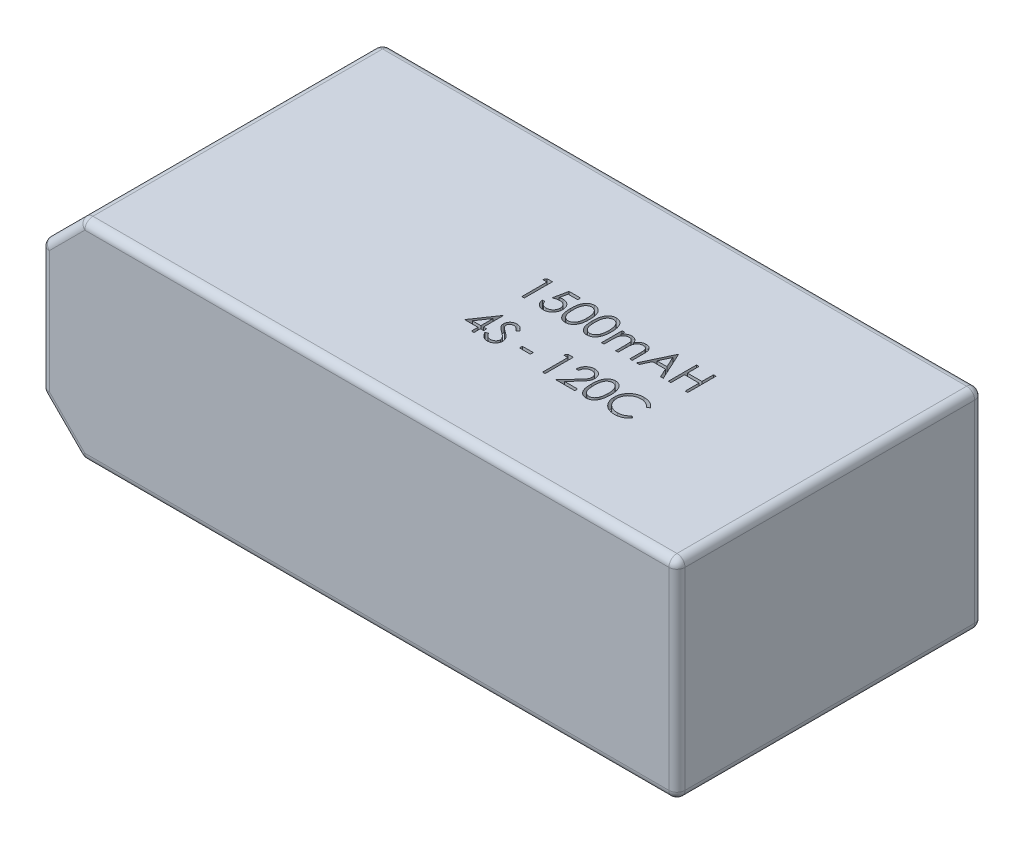
SolidWorks part; units mm, degrees
ref_plane "Front Plane" through (0, 0, 0) normal (0, 0, 1) x (1, 0, 0)
ref_plane "Top Plane" through (0, 0, 0) normal (0, 1, 0) x (1, 0, 0)
ref_plane "Right Plane" through (0, 0, 0) normal (1, 0, 0) x (0, 0, -1)
sketch "Sketch1" plane through (0, 0, 0) normal (0, 1, 0) x (1, 0, 0)
  line L1 (-39.5, -19) -> (39.5, -19)
  line L2 (-39.5, -19) -> (-39.5, 19)
  line L3 (-39.5, 19) -> (39.5, 19)
  line L4 (39.5, -19) -> (39.5, 19)
  line L5 (-39.5, -19) -> (39.5, 19) construction
  line L6 (-39.5, 19) -> (39.5, -19) construction
  point P0 (0, 0)
  dimension "D1" = 79
  dimension "D2" = 38
extrude "Boss-Extrude1" add sketch "Sketch1" along normal mid plane 26
chamfer "Chamfer1" distance 5 angle 45 2 edges at (-39.5, 13, 0) (-39.5, -13, 0)
fillet "Fillet1" radius 1 18 edges at (39.5, -13, 0) (39.5, 13, 0) (-37, -10.5, -19) (-39.5, 0, -19) (-37, 10.5, -19) (2.5, -13, -19) (39.5, 0, -19) (2.5, 13, -19) (-37, -10.5, 19) (-39.5, 0, 19) (-37, 10.5, 19) (39.5, 0, 19) (2.5, 13, 19) (2.5, -13, 19) (-34.5, -13, 0) (-39.5, -8, 0) (-34.5, 13, 0) (-39.5, 8, 0)
sketch "Sketch2" plane through (0, 13, 0) normal (0, 1, 0) x (1, 0, 0)
  text T0 "1500mAH\r\n4S - 120C"
extrude "Cut-Extrude1" cut sketch "Sketch2" against normal blind 1
